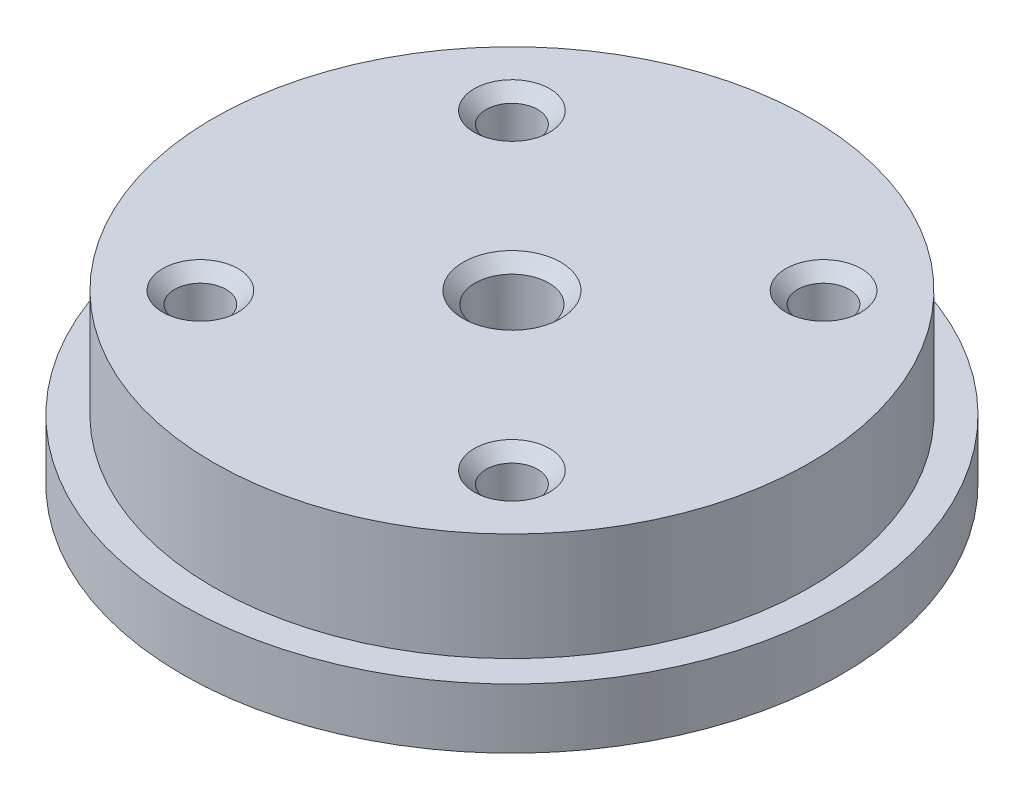
SolidWorks part; units mm, degrees
ref_plane "Ebene vorne" through (0, 0, 0) normal (0, 0, 1) x (1, 0, 0)
ref_plane "Ebene oben" through (0, 0, 0) normal (0, 1, 0) x (1, 0, 0)
ref_plane "Ebene rechts" through (0, 0, 0) normal (1, 0, 0) x (0, 0, -1)
sketch "Skizze1" plane through (0, 0, 0) normal (0, 0, 1) x (1, 0, 0)
  line L0 (0, 0) -> (0, -19285.6295) construction
  line L1 (10.6, 0) -> (27.5, 0)
  line L2 (27.5, 0) -> (27.5, 5)
  line L3 (27.5, 5) -> (24.9, 5)
  line L4 (24.9, 5) -> (24.9, 14)
  line L5 (24.9, 14) -> (0, 14)
  line L6 (0, 14) -> (0, 5.5)
  line L7 (0, 5.5) -> (7.5, 5.5)
  line L8 (10.6, 5) -> (10.6, 0)
  line L9 (7.5, 5.5) -> (7.5, 5)
  line L10 (7.5, 5) -> (10.6, 5)
  dimension "D1" = 49.8
  dimension "D2" = 21.2
  dimension "D3" = 55
  dimension "D4" = 5
  dimension "D5" = 0.5
  dimension "D6" = 15
  dimension "D7" = 5
  dimension "D8" = 14
revolve "Rotation1" add sketch "Skizze1" angle 360 about L0
hole_wizard "Ø2.5 (2.5) Durchmesser Bohrung1" positions "Skizze2" profile "Skizze3" hole size "Ø2.5" standard "DIN"
sketch "Skizze2" plane through (0, 0, 0) normal (0, -1, 0) x (-1, 0, 0)
  circle A0 centre (0, 0) radius 18.5 construction
  point P5 (0, 18.5)
  point P12 (16.0215, 9.25)
  point P13 (16.0215, -9.25)
  point P14 (0, -18.5)
  point P15 (-16.0215, -9.25)
  point P16 (-16.0215, 9.25)
  dimension "D1" = 37
sketch "Skizze3" plane through (16.0215, 0, -9.25) normal (1, 0, 0) x (0, 0, -1)
  line L0 (0, 0) -> (0, 9.7511)
  line L1 (0, 9.7511) -> (1.25, 9)
  line L2 (1.25, 9) -> (1.25, 0.375)
  line L3 (1.25, 0.375) -> (1.625, 0)
  line L5 (1.625, 0) -> (0, 0)
  line L6 (-1.25, 0.375) -> (-1.625, 0) construction
  line L10 (0, 9.7511) -> (-1.25, 9) construction
  line L11 (0, -6.35) -> (0, 107.95) construction
  dimension "Bohrerdurchmesser" = 2.5
  dimension "Bohrungstiefe" = 9
  dimension "Senkdurchmesser2 (Oben)" = 3.25
  dimension "Senkwinkel2 (Oben)" = 90
  dimension "Spitzenwinkel" = 118
sketch "Skizze5" plane through (0, 14, 0) normal (0, 1, 0) x (1, 0, 0)
  line L1 (-13, -13) -> (13, -13) construction
  line L2 (-13, -13) -> (-13, 13) construction
  line L3 (-13, 13) -> (13, 13) construction
  line L4 (13, -13) -> (13, 13) construction
  line L5 (-13, -13) -> (13, 13) construction
  line L6 (-13, 13) -> (13, -13) construction
  circle A0 centre (0, 0) radius 3.075
  circle A1 centre (13, 13) radius 2.15
  circle A2 centre (13, -13) radius 2.15
  circle A3 centre (-13, -13) radius 2.15
  circle A4 centre (-13, 13) radius 2.15
  dimension "D1" = 6.15
  dimension "D3" = 4.3
  dimension "D2" = 26
extrude "Schnitt-Linear austragen1" cut sketch "Skizze5" against normal blind 9
chamfer "Fase1" distance 1 angle 45 5 edges at (13, 14, 15.15) (13, 14, -10.85) (-13, 14, -10.85) (0, 14, 3.075) (-13, 14, 15.15)
